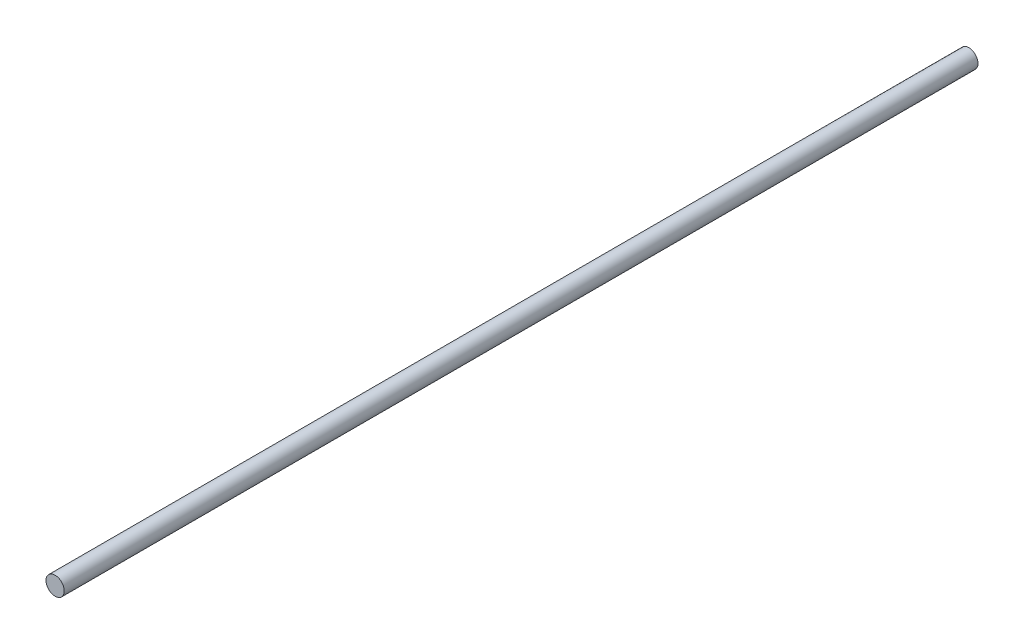
SolidWorks part; units mm, degrees
ref_plane "前视基准面" through (0, 0, 0) normal (0, 0, 1) x (1, 0, 0)
ref_plane "上视基准面" through (0, 0, 0) normal (0, 1, 0) x (1, 0, 0)
ref_plane "右视基准面" through (0, 0, 0) normal (1, 0, 0) x (0, 0, -1)
sketch "草图1" plane through (0, 0, 0) normal (0, 0, 1) x (1, 0, 0)
  circle A0 centre (0, 0) radius 1
  dimension "D1" = 2
extrude "凸台-拉伸1" add sketch "草图1" along normal mid plane 100 contours A0
